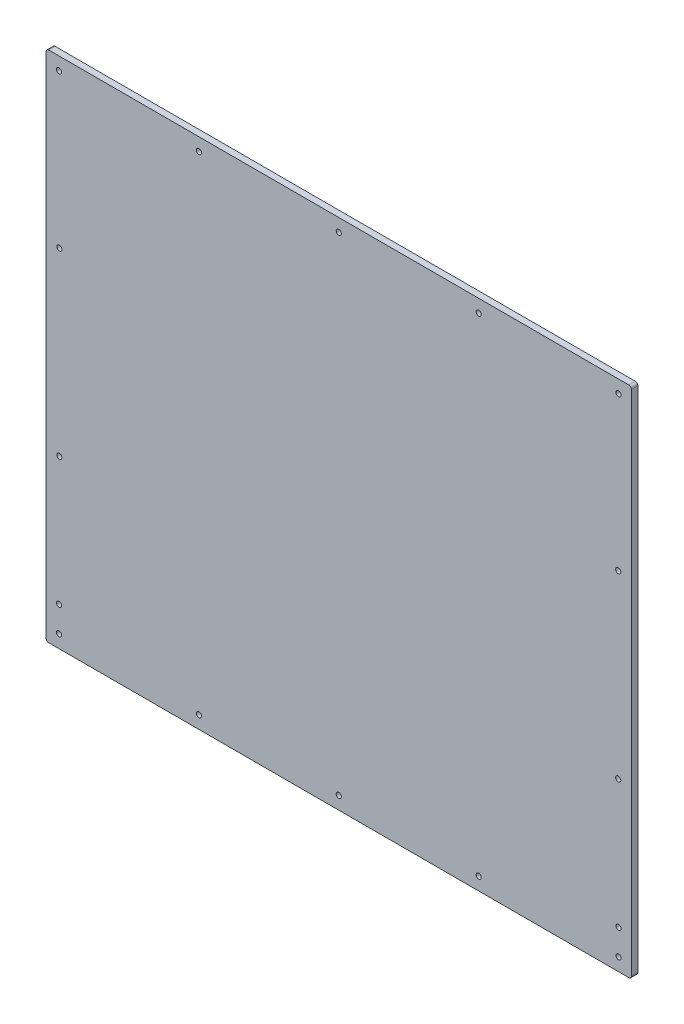
SolidWorks part; units mm, degrees
ref_plane "Plan de face" through (0, 0, 0) normal (0, 0, 1) x (1, 0, 0)
ref_plane "Plan de dessus" through (0, 0, 0) normal (0, 1, 0) x (1, 0, 0)
ref_plane "Plan de droite" through (0, 0, 0) normal (1, 0, 0) x (0, 0, -1)
sketch "Esquisse1" plane through (0, 0, 0) normal (0, 0, 1) x (1, 0, 0)
  line L1 (-452, -400) -> (452, -400)
  line L2 (-456, -396) -> (-456, 396)
  line L3 (-452, 400) -> (452, 400)
  line L4 (456, -396) -> (456, 396)
  line L5 (-456, -400) -> (456, 400) construction
  line L6 (-456, 400) -> (456, -400) construction
  line L7 (0, 400) -> (0, -400) construction
  line L8 (-456, 0) -> (456, 0) construction
  arc A0 (-456, 396) -> (-452, 400) centre (-452, 396) cw
  arc A1 (456, 396) -> (452, 400) centre (452, 396) ccw
  arc A2 (452, -400) -> (456, -396) centre (452, -396) ccw
  arc A3 (-456, -396) -> (-452, -400) centre (-452, -396) ccw
  circle A4 centre (436, 380) radius 4
  circle A5 centre (435.5, -140) radius 4
  circle A6 centre (435.5, 141) radius 4
  circle A7 centre (-435.5, -140) radius 4
  circle A8 centre (-436, 380) radius 4
  circle A9 centre (-435.5, 141) radius 4
  circle A10 centre (436, -380) radius 4
  circle A11 centre (436, -340) radius 4
  circle A12 centre (-436, -340) radius 4
  circle A13 centre (-436, -380) radius 4
  circle A14 centre (218, -380) radius 4
  circle A15 centre (0, -380) radius 4
  circle A16 centre (-218, -380) radius 4
  circle A17 centre (-218, 380) radius 4
  circle A18 centre (0, 380) radius 4
  circle A19 centre (218, 380) radius 4
  point P0 (0, 0)
  dimension "D3" = 4
  dimension "D4" = 4
  dimension "D5" = 4
  dimension "D6" = 4
  dimension "D7" = 8
  dimension "D8" = 20
  dimension "D9" = 20
  dimension "D11" = 20.5
  dimension "D12" = 259
  dimension "D13" = 8
  dimension "D14" = 2
  dimension "D1" = 912
  dimension "D2" = 800
  dimension "D15" = 4
  dimension "D10" = 2
extrude "Boss.-Extru.1" add sketch "Esquisse1" along normal blind 10
